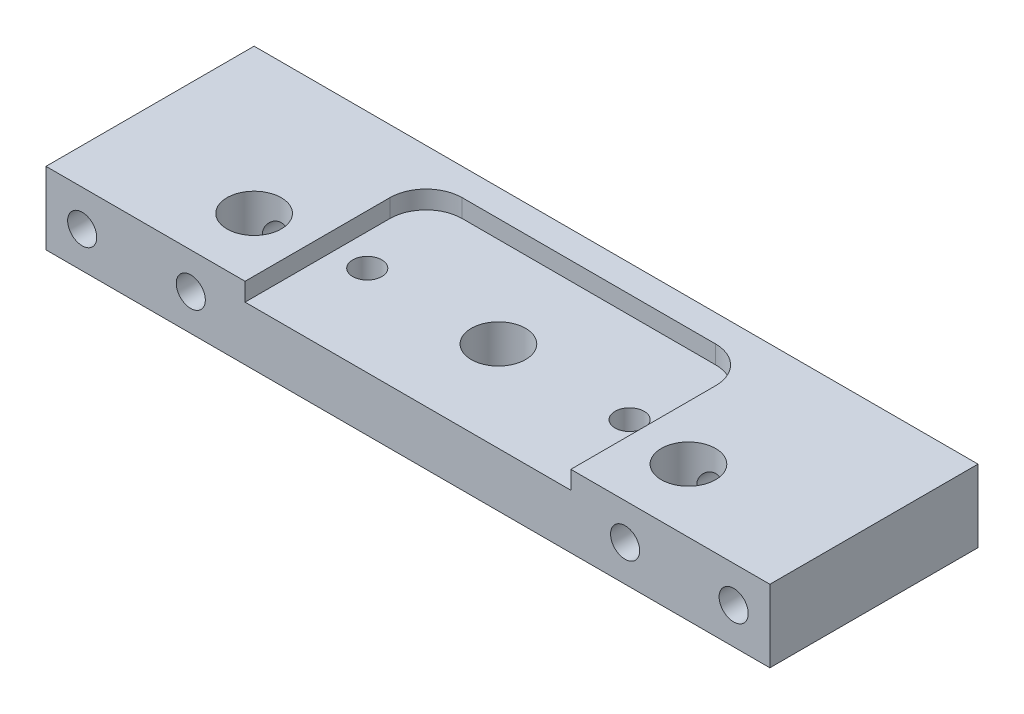
SolidWorks part; units mm, degrees
material "6061 Alloy"
ref_plane "Front Plane" through (0, 0, 0) normal (0, 0, 1) x (1, 0, 0)
ref_plane "Top Plane" through (0, 0, 0) normal (0, 1, 0) x (1, 0, 0)
ref_plane "Right Plane" through (0, 0, 0) normal (1, 0, 0) x (0, 0, -1)
sketch "Sketch1" plane through (0, 0, 0) normal (0, 1, 0) x (1, 0, 0)
  line L1 (-63.5, 25.4) -> (63.5, 25.4)
  line L2 (-63.5, 25.4) -> (-63.5, -25.4)
  line L3 (-63.5, -25.4) -> (63.5, -25.4)
  line L4 (63.5, 25.4) -> (63.5, -25.4)
  line L5 (-63.5, 25.4) -> (63.5, -25.4) construction
  line L6 (-63.5, -25.4) -> (63.5, 25.4) construction
  point P0 (0, 0)
  dimension "D1" = 127
  dimension "D2" = 50.8
extrude "Boss-Extrude1" add sketch "Sketch1" along normal mid plane 12.7
hole_wizard "Tapped Hole for #10-32 Helicoil1" positions "Sketch3" profile "Sketch2" tap size "#10-32" standard "Helicoil® Inch" end condition up to next
sketch "Sketch3" plane through (0, 0, -25.4) normal (0, 0, -1) x (-1, 0, 0)
  line L0 (-63.5, 0) -> (63.5, 0) construction
  line L1 (-63.5, 6.35) -> (-63.5, -6.35) construction
  line L2 (63.5, 6.35) -> (63.5, -6.35) construction
  point P8 (-57.15, 0)
  point P12 (57.15, 0)
  dimension "D1" = 6.35
  dimension "D2" = 6.35
cosmetic thread "Hole Thread1" parameters "D1"=11.43, "D2"=5.936
cosmetic thread "Hole Thread3" parameters "D1"=11.43, "D2"=5.936
sketch "Sketch2" plane through (57.15, 0, -25.4) normal (1, 0, 0) x (0, 1, 0)
  line L0 (0, 0) -> (0, 50.8)
  line L1 (0, 50.8) -> (2.5527, 50.8)
  line L2 (2.5527, 50.8) -> (2.5527, 0)
  line L5 (2.5527, 0) -> (0, 0)
  line L11 (0, -6.35) -> (0, 107.95) construction
  dimension "Thru Tap Drill Dia." = 5.1054
  dimension "Thru Tap Drill Depth" = 50.8
sketch "Sketch7" plane through (0, 6.35, 0) normal (0, 1, 0) x (1, 0, 0)
  line L0 (63.5, -25.4) -> (63.5, 25.4) construction
  line L1 (-63.5, -25.4) -> (63.5, -25.4)
  line L2 (-63.5, -25.4) -> (-63.5, -11.1125)
  line L3 (-63.5, -11.1125) -> (63.5, -11.1125)
  line L4 (63.5, -25.4) -> (63.5, -11.1125)
  line L5 (63.5, 25.4) -> (-63.5, 25.4) construction
  dimension "D1" = 36.5125
extrude "Cut-Extrude2" cut sketch "Sketch7" against normal through all
hole_wizard "Tapped Hole for #10-32 Helicoil3" positions "Sketch17" profile "Sketch16" tap size "#10-32" standard "Helicoil® Inch"
sketch "Sketch17" plane through (0, 0, 11.1125) normal (0, 0, 1) x (1, 0, 0)
  line L0 (-63.5, 0) -> (63.5, 0) construction
  line L1 (-63.5, -6.35) -> (-63.5, 6.35) construction
  line L2 (63.5, -6.35) -> (63.5, 6.35) construction
  point P8 (-38.1, 0)
  point P10 (38.1, 0)
  dimension "D1" = 25.4
  dimension "D2" = 25.4
sketch "Sketch16" plane through (-38.1, 0, 11.1125) normal (1, 0, 0) x (0, -1, 0)
  line L0 (0, 0) -> (0, 38.0453)
  line L1 (0, 38.0453) -> (2.5527, 36.5115)
  line L2 (2.5527, 36.5115) -> (2.5527, 0)
  line L5 (2.5527, 0) -> (0, 0)
  line L10 (0, 38.0453) -> (-2.5527, 36.5115) construction
  line L11 (0, -6.35) -> (0, 107.95) construction
  dimension "Tap Drill Dia." = 5.1054
  dimension "Tap Drill Depth" = 36.5115
  dimension "Drill Angle" = 118
sketch "Sketch4" plane through (0, 6.35, 0) normal (0, 1, 0) x (1, 0, 0)
  line L0 (-38.1, 0) -> (38.1, 0) construction
  line L1 (0, 0) -> (0, 4.7625) construction
  line L2 (63.5, 25.4) -> (-63.5, 25.4) construction
  line L4 (63.5, 25.4) -> (-63.5, 25.4) construction
  circle A0 centre (-38.1, 0) radius 4.7625
  circle A1 centre (38.1, 0) radius 4.7625
  circle A2 centre (0, 4.7625) radius 4.7625
  dimension "D1" = 9.525
  dimension "D4" = 9.525
  dimension "D5" = 20.6375
  dimension "D3" = 76.2
  dimension "D2" = 25.4
extrude "Cut-Extrude1" cut sketch "Sketch4" against normal through all
sketch "Sketch12" [suppressed] plane through (0, -6.35, 0) normal (0, -1, 0) x (1, 0, 0)
  line L0 (-63.5, -25.4) -> (-63.5, 25.4) construction
  line L1 (63.5, 25.4) -> (-63.5, 25.4)
  line L2 (63.5, 25.4) -> (63.5, 11.1125)
  line L3 (63.5, 11.1125) -> (-63.5, 11.1125)
  line L4 (-63.5, 25.4) -> (-63.5, 11.1125)
  line L5 (63.5, -25.4) -> (-63.5, -25.4) construction
  dimension "D1" = 36.5125
extrude "Cut-Extrude5" [suppressed] cut sketch "Sketch12" against normal through all
sketch "Sketch8" [suppressed] plane through (0, -6.35, 0) normal (0, -1, 0) x (1, 0, 0)
  line L0 (-25.4, 11.1125) -> (25.4, 11.1125)
  line L1 (-63.5, 11.1125) -> (63.5, 11.1125) construction
  line L2 (-25.4, 11.1125) -> (-25.4, -13.1191)
  line L3 (-19.05, -19.4691) -> (19.05, -19.4691)
  line L4 (25.4, 11.1125) -> (25.4, -13.1191)
  line L5 (-25.4, 11.1125) -> (25.4, -19.4691) construction
  line L6 (-25.4, -19.4691) -> (25.4, 11.1125) construction
  arc A0 (-25.4, -13.1191) -> (-19.05, -19.4691) centre (-19.05, -13.1191) ccw
  arc A1 (19.05, -19.4691) -> (25.4, -13.1191) centre (19.05, -13.1191) ccw
  point P0 (0, -4.1783)
  dimension "D3" = 6.35
  dimension "D1" = 24.2316
  dimension "D2" = 50.8
extrude "Cut-Extrude3" [suppressed] cut sketch "Sketch8" against normal blind 3.175
hole_wizard "#10 Clearance Hole1" [suppressed] positions "Sketch10" profile "Sketch9" hole size "#10" standard "ANSI Inch"
sketch "Sketch10" plane through (0, -3.175, 0) normal (0, -1, 0) x (-1, 0, 0)
  circle A1 centre (0, 13.1191) radius 19.05 construction
  circle A4 centre (0, 4.7625) radius 4.7625 construction
  point P6 (19.05, 13.1191)
  point P8 (-19.05, 13.1191)
  dimension "D2" = 38.1
  dimension "D1" = 8.3566
sketch "Sketch9" plane through (-19.05, -3.175, -13.1191) normal (1, 0, 0) x (0, 0, -1)
  line L0 (0, 0) -> (0, 9.525)
  line L1 (0, 9.525) -> (2.5527, 9.525)
  line L2 (2.5527, 9.525) -> (2.5527, 0)
  line L5 (2.5527, 0) -> (0, 0)
  line L11 (0, -6.35) -> (0, 107.95) construction
  dimension "Thru Hole Dia." = 5.1054
  dimension "Thru Hole Depth" = 38.1
sketch "Sketch11" plane through (0, 6.35, 0) normal (0, 1, 0) x (1, 0, 0)
  line L0 (63.5, -11.1125) -> (-63.5, -11.1125) construction
  line L1 (-22.225, 20.6375) -> (22.225, 20.6375)
  line L2 (-28.575, 14.2875) -> (-28.575, -11.1125)
  line L3 (-28.575, -11.1125) -> (28.575, -11.1125)
  line L4 (28.575, 14.2875) -> (28.575, -11.1125)
  line L5 (-28.575, 20.6375) -> (28.575, -11.1125) construction
  line L6 (-28.575, -11.1125) -> (28.575, 20.6375) construction
  arc A0 (22.225, 20.6375) -> (28.575, 14.2875) centre (22.225, 14.2875) cw
  arc A1 (-22.225, 20.6375) -> (-28.575, 14.2875) centre (-22.225, 14.2875) ccw
  circle A3 centre (0, 4.7625) radius 4.7625 construction
  point P0 (0, 4.7625)
  dimension "D3" = 6.35
  dimension "D1" = 15.875
  dimension "D2" = 57.15
extrude "Cut-Extrude4" cut sketch "Sketch11" against normal blind 3.175
hole_wizard "Tapped Hole for #10-32 Helicoil2" [suppressed] positions "Sketch15" profile "Sketch14" tap size "#10-32" standard "Helicoil® Inch"
sketch "Sketch15" plane through (0, 0, 11.1125) normal (0, 0, 1) x (1, 0, 0)
  line L0 (-63.5, 0) -> (63.5, 0) construction
  line L1 (-63.5, 6.35) -> (-63.5, -6.35) construction
  line L2 (63.5, 6.35) -> (63.5, -6.35) construction
  point P8 (-38.1, 0)
  point P10 (38.1, 0)
  dimension "D1" = 25.4
  dimension "D2" = 25.4
sketch "Sketch14" plane through (-38.1, 0, 11.1125) normal (1, 0, 0) x (0, -1, 0)
  line L0 (0, 0) -> (0, 14.2338)
  line L1 (0, 14.2338) -> (2.5527, 12.7)
  line L2 (2.5527, 12.7) -> (2.5527, 0)
  line L5 (2.5527, 0) -> (0, 0)
  line L10 (0, 14.2338) -> (-2.5527, 12.7) construction
  line L11 (0, -6.35) -> (0, 107.95) construction
  dimension "Tap Drill Dia." = 5.1054
  dimension "Tap Drill Depth" = 12.7
  dimension "Drill Angle" = 118
chamfer "Chamfer1" [suppressed] distance 0.508 angle 45
chamfer "Chamfer2" [suppressed] distance 0.508 angle 45
hole_wizard "#10 Clearance Hole2" [suppressed] positions "Sketch19" profile "Sketch18" hole size "#10" standard "ANSI Inch"
sketch "Sketch19" [suppressed] plane through (0, 3.175, 0) normal (0, 1, 0) x (1, 0, 0)
  circle A0 centre (0, 4.7625) radius 23.0099 construction
  point P4 (-23.0099, 4.7625)
  point P6 (23.0099, 4.7625)
  dimension "D1" = 46.0197
sketch "Sketch18" plane through (-23.0099, 3.175, -4.7625) normal (1, 0, 0) x (0, 0, 1)
  line L0 (0, 0) -> (0, 11.1858)
  line L1 (0, 11.1858) -> (2.5527, 9.652)
  line L2 (2.5527, 9.652) -> (2.5527, 0)
  line L5 (2.5527, 0) -> (0, 0)
  line L10 (0, 11.1858) -> (-2.5527, 9.652) construction
  line L11 (0, -6.35) -> (0, 107.95) construction
  dimension "Hole Dia." = 5.1054
  dimension "Hole Depth" = 9.652
  dimension "Drill Angle" = 118
hole_wizard "#10 Clearance Hole3" positions "Sketch22" profile "Sketch23" hole size "#10" standard "ANSI Inch"
sketch "Sketch22" plane through (0, 3.175, 0) normal (0, 1, 0) x (1, 0, 0)
  line L0 (-23.0124, 4.7625) -> (23.0124, 4.7625) construction
  line L2 (0, 4.7625) -> (0, 0) construction
  circle A0 centre (0, 4.7625) radius 4.7625 construction
  point P0 (-23.0124, 4.7625)
  point P1 (23.0124, 4.7625)
  dimension "D1" = 46.0248
sketch "Sketch23" plane through (-23.0124, 3.175, -4.7625) normal (1, 0, 0) x (0, 0, 1)
  line L0 (0, 0) -> (0, 14.2338)
  line L1 (0, 14.2338) -> (2.5527, 12.7)
  line L2 (2.5527, 12.7) -> (2.5527, 0)
  line L5 (2.5527, 0) -> (0, 0)
  line L10 (0, 14.2338) -> (-2.5527, 12.7) construction
  line L11 (0, -6.35) -> (0, 107.95) construction
  dimension "Hole Dia." = 5.1054
  dimension "Hole Depth" = 12.7
  dimension "Drill Angle" = 118
